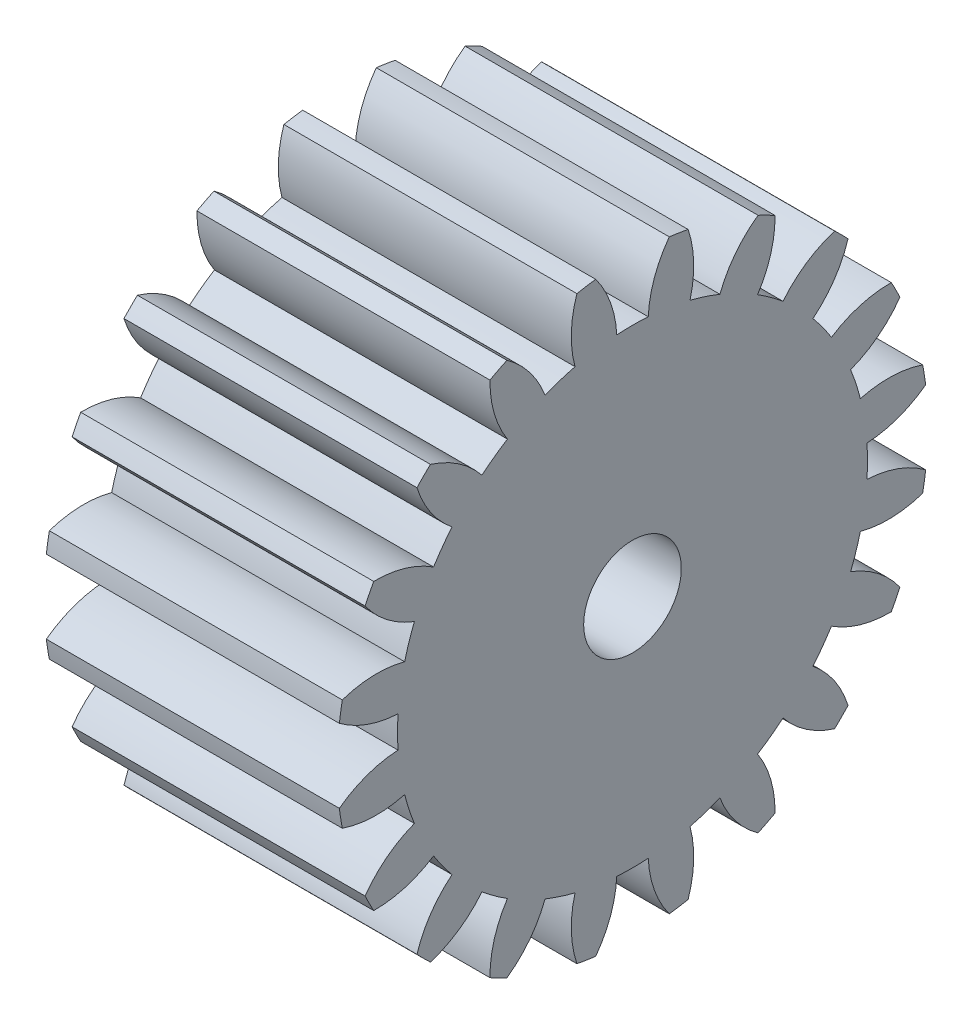
SolidWorks part; units mm, degrees
ref_plane "Plane1" through (0, 0, 0) normal (0, 0, 1) x (1, 0, 0)
ref_plane "Plane2" through (0, 0, 0) normal (0, 1, 0) x (1, 0, 0)
ref_plane "Plane3" through (0, 0, 0) normal (1, 0, 0) x (0, 0, -1)
sketch "HoldingSke" plane through (0, 0, 0) normal (0, 1, 0) x (1, 0, 0)
  line L0 (0, 0) -> (0.6834, -0.2487)
  line L1 (-15, 0) -> (100, 0) construction
  line L2 (0, 0) -> (-2.1039, 2.3779)
  line L3 (0, 0) -> (-11.863, 4.5341)
  line L4 (0, 0) -> (8.1152, 2.9537)
  line L5 (0, 0) -> (-46.8476, -17.4728)
  line L6 (0, 0) -> (-12.4344, -8.3896)
  line L7 (-2.1039, 2.3779) -> (8.6586, 51.2059)
  line L8 (-76.2, 54.61) -> (-75.3, 54.61)
  line L9 (-67.7845, 28.3722) -> (-49.3413, 33.142)
  line L10 (-76.2, 71.12) -> (104.1128, 71.12)
  line L11 (0, 0) -> (-15, 0)
  line L12 (-76.2, 101.6) -> (-76.151, 101.6)
  line L13 (24.9733, 27.94) -> (52.9518, 28.4284)
  line L14 (24.9733, 27.94) -> (24.9743, 27.94)
  line L15 (24.9733, 27.94) -> (100.4006, 29.5858)
  line L16 (-63.627, -1.375) -> (-12.827, -1.375)
  circle A0 centre (0, 0) radius 2.5
  circle A1 centre (0, 0) radius 12.0303
  circle A2 centre (0, 0) radius 37.5
  circle A3 centre (0, 0) radius 2.5
  dimension "MHD" = 24.0605
  dimension "Hub_dia" = 75
  dimension "Bore" = 5
  dimension "MBD" = 5
  dimension "Num_teeth" = 20
  dimension "Pitch" = 0.7273
  dimension "Overall_len" = 50
  dimension "Show_teeth" = 20
  dimension "Thickness" = 15
  dimension "OAL" = 50.0001
  dimension "T_dim" = 0.9
  dimension "Ap" = 14.5
  dimension "H" = 19.05
  dimension "Pitch_radius" = 180.3128
  dimension "Width" = 15
  dimension "Backlash" = 0.049
  dimension "Addendum_fac" = 1
  dimension "Dedendum_fac" = 1.25
  dimension "Clearance_fac" = 0.25
  dimension "Dedendum_add" = 0.001
  dimension "Module" = 1.375
sketch "BasProSke" plane through (0, 0, 0) normal (0, 1, 0) x (1, 0, 0)
  line L0 (-10, 0) -> (60, 0) construction
  line L1 (0, 0) -> (0, 15.125)
  line L2 (0, 0) -> (15, 0)
  line L3 (15, 0) -> (15, 15.125)
  line L4 (15, 15.125) -> (0, 15.125)
  dimension "Thickness" = 15
  dimension "Diameter" = 30.25
revolve "Base-Revolve" add sketch "BasProSke" angle 360 about L0
sketch "TooCutSke" plane through (0, 0, 0) normal (1, 0, 0) x (0, 0, -1)
  line L1 (0, 0) -> (0, 107) construction
  line L2 (0, 0) -> (-1.1645, 13.7006) construction
  line L3 (0, 0) -> (-4.2907, 27.0905) construction
  line L4 (-1.1645, 13.7006) -> (-2.1454, 13.5452) construction
  arc A0 (0.8054, 12.0033) -> (-0.8054, 12.0033) centre (0, 0) ccw
  arc A1 (1.9007, 15.0307) -> (-1.9007, 15.0307) centre (0, 0) ccw
  circle A2 centre (0, 0) radius 13.75 construction
  circle A3 centre (0, 0) radius 13.312 construction
  arc A4 (-0.8054, 12.0033) -> (-1.9007, 15.0307) centre (-6.2985, 11.7277) ccw
  arc A5 (1.9007, 15.0307) -> (0.8054, 12.0033) centre (6.2985, 11.7277) ccw
  dimension "Root_dia" = 24.0605
  dimension "Overcut_dia" = 30.3008
  dimension "Pitch_dia" = 27.5
  dimension "Base_dia" = 26.6241
  dimension "Flank_rad" = 5.5
  dimension "Half_ang" = 9
  dimension "Half_CT" = 0.9931
extrude "ToothCut" cut sketch "TooCutSke" along normal through all
fillet "Breaks" [suppressed] radius 0.0275
fillet "RootFillets" [suppressed] radius 0.3448
pattern_circular "TeethCuts" count 20 over 360 about axis through (0, 0, 0) along (1, 0, 0) of "ToothCut", "RootFillets", "Breaks"
sketch "HubNeaOneSke" plane through (0, 0, 0) normal (-1, 0, 0) x (0, 0, 1)
  circle A0 centre (0, 0) radius 12.0303
  dimension "Diameter" = 24.0605
extrude "HubNearOne" [suppressed] add sketch "HubNeaOneSke" along normal blind 35.0001
sketch "HubNeaBotSke" plane through (0, 0, 0) normal (-1, 0, 0) x (0, 0, 1)
  circle A0 centre (0, 0) radius 12.0303
  dimension "Diameter" = 24.0605
extrude "HubNearBoth" [suppressed] add sketch "HubNeaBotSke" along normal blind 17.5
ref_plane "FarPln" through (15, 0, 0) normal (1, 0, 0) x (0, 0, -1)
sketch "HubFarSke" plane through (15, 0, 0) normal (1, 0, 0) x (0, 0, -1)
  circle A0 centre (0, 0) radius 12.0303
  dimension "Diameter" = 24.0605
extrude "HubFar" [suppressed] add sketch "HubFarSke" along normal blind 17.5
sketch "BorSke" plane through (0, 0, 0) normal (1, 0, 0) x (0, 0, -1)
  circle A0 centre (0, 0) radius 2.5
  dimension "Diameter" = 5
extrude "Bore" cut sketch "BorSke" along normal mid plane 100.0001
sketch "KeySke" plane through (0, 0, 0) normal (1, 0, 0) x (0, 0, -1)
  line L0 (-1, 0) -> (-1, 3.4)
  line L1 (-1, 3.4) -> (1, 3.4)
  line L2 (1, 3.4) -> (1, 0)
  line L3 (0, 0) -> (0, 34) construction
  line L4 (-1, 0) -> (1, 0)
  dimension "Offset" = 3.4
  dimension "Width" = 2
extrude "Keyway" [suppressed] cut sketch "KeySke" along normal mid plane 100.0001
pattern_circular "Keyway2" [suppressed] count 2 every 90 about axis through (-10, 0, 0) along (1, 0, 0)
equation "' \"Module@HoldingSke\" = 6.35"
equation "' \"Num_teeth@HoldingSke\" = 12"
equation "' \"Ap@HoldingSke\" =  20"
equation "' \"Ap@HoldingSke\" = 20"
equation "' \"Width@HoldingSke\" = 0.5 * 25.4"
equation "' \"Hub_dia@HoldingSke\"= 1 * 25.4"
equation "' \"Hub_dia@HoldingSke\" = 1 * 25.4"
equation "' \"Overall_len@HoldingSke\" = 1.0 * 25.4"
equation "' \"Bore@HoldingSke\" = 0.75 * 25.4"
equation "' \"T_dim@HoldingSke\" = 0.1 * 25.4"
equation "' \"Width@KeySke\" = 0.25 * 25.4"
equation "' \"Show_teeth@HoldingSke\" = 13"
equation "' \"Backlash@HoldingSke\" = 0.009 * 25.4"
equation "' \"Addendum_fac@HoldingSke\" = 1.0"
equation "' \"Dedendum_fac@HoldingSke\" = 1.25"
equation "' \"Dedendum_add@HoldingSke\" = 0.00005 * 25.4"
equation "' \"Clearance_fac@HoldingSke\" = 0.25"
equation "\"Pitch@HoldingSke\" = 1 / \"Module@HoldingSke\""
equation "\"Overcut_dia@TooCutSke\" = (\"Num_teeth@HoldingSke\" + 2 * \"Addendum_fac@HoldingSke\") / \"Pitch@HoldingSke\" + 0.002 * 25.4"
equation "\"Pitch_dia@TooCutSke\" = \"Num_teeth@HoldingSke\" / \"Pitch@HoldingSke\""
equation "\"Base_dia@TooCutSke\" = \"Num_teeth@HoldingSke\" / \"Pitch@HoldingSke\" * cos((\"Ap@HoldingSke\"  * 3.14159265 / 180))"
equation "\"Root_dia@TooCutSke\" = (\"Num_teeth@HoldingSke\" + 2) / \"Pitch@HoldingSke\" - 2 * (\"Addendum_fac@HoldingSke\" + \"Dedendum_fac@HoldingSke\") / \"Pitch@HoldingSke\" - \"Dedendum_add@HoldingSke\" * 2"
equation "\"Half_ang@TooCutSke\" = 180 / \"Num_teeth@HoldingSke\""
equation "\"Half_CT@TooCutSke\" = \"Num_teeth@HoldingSke\" / \"Pitch@HoldingSke\" * sin((3.14159265 / 2 / \"Num_teeth@HoldingSke\")) / 2 - 7 * \"Backlash@HoldingSke\" / 4"
equation "\"Flank_rad@TooCutSke\" = \"Num_teeth@HoldingSke\" / \"Pitch@HoldingSke\" / 5"
equation "\"Radius@RootFillets\" = \"Clearance_fac@HoldingSke\" / \"Pitch@HoldingSke\" + \"Dedendum_add@HoldingSke\""
equation "\"Break_rad@Breaks\" = 0.02 / \"Pitch@HoldingSke\""
equation "\"Thickness@HoldingSke\" = \"Width@HoldingSke\""
equation "\"OAL@HoldingSke\" = \"Thickness@HoldingSke\""
equation "\"MHD@HoldingSke\" = (\"Num_teeth@HoldingSke\" + 2) / \"Pitch@HoldingSke\" - 2 * (\"Addendum_fac@HoldingSke\" + \"Dedendum_fac@HoldingSke\")  / \"Pitch@HoldingSke\" - \"Dedendum_add@HoldingSke\" * 2"
equation "\"MBD@HoldingSke\" = (\"Num_teeth@HoldingSke\" + 2) / \"Pitch@HoldingSke\" - 2 * (\"Addendum_fac@HoldingSke\" + \"Dedendum_fac@HoldingSke\")  / \"Pitch@HoldingSke\" - \"Dedendum_add@HoldingSke\" * 2 - 0.002 * 25.4"
equation "\"MHD@HoldingSke\" = ((sgn( \"MHD@HoldingSke\" - \"Hub_dia@HoldingSke\" )-1)*( \"MHD@HoldingSke\" - \"Hub_dia@HoldingSke\" ))/-2+ \"Hub_dia@HoldingSke\""
equation "\"MBD@HoldingSke\" = ((sgn( \"MBD@HoldingSke\" - \"Bore@HoldingSke\" )-1)*( \"MBD@HoldingSke\" - \"Bore@HoldingSke\" ))/-2+ \"Bore@HoldingSke\""
equation "\"OAL@HoldingSke\" = ((sgn( \"OAL@HoldingSke\" - \"Overall_len@HoldingSke\" )+1)*( \"OAL@HoldingSke\" - \"Overall_len@HoldingSke\" ))/2 + \"Overall_len@HoldingSke\" + 0.000002 * 25.4"
equation "\"Num_teeth@TeethCuts\" = int( \"Show_teeth@HoldingSke\" ) + 1"
equation "\"Num_teeth@TeethCuts\" = ((sgn( \"Num_teeth@TeethCuts\" - \"Num_teeth@HoldingSke\" )-1)*( \"Num_teeth@TeethCuts\" - \"Num_teeth@HoldingSke\" ))/-2+ \"Num_teeth@HoldingSke\""
equation "\"Num_teeth@TeethCuts\" = ((sgn( \"Num_teeth@TeethCuts\" - 2.0)+1)*( \"Num_teeth@TeethCuts\" - 2.0))/2 +2.0"
equation "\"Angle@TeethCuts\" = 360.0 / \"Num_teeth@HoldingSke\""
equation "\"Diameter@BasProSke\" = (\"Num_teeth@HoldingSke\" + 2 * \"Addendum_fac@HoldingSke\") / \"Pitch@HoldingSke\""
equation "\"Thickness@BasProSke\"  = \"Thickness@HoldingSke\""
equation "' \"Fillet_rad@BasProSke\" =  \"Thickness@HoldingSke\" * 0.05"
equation "' \"Fillet_rad@BasProSke\" = \"Thickness@HoldingSke\" * 0.05"
equation "\"MHD@HoldingSke\" = ((sgn( \"MHD@HoldingSke\" - \"Root_dia@TooCutSke\" )-1)*( \"MHD@HoldingSke\" - \"Root_dia@TooCutSke\" ))/-2+ \"Root_dia@TooCutSke\""
equation "\"Diameter@HubNeaOneSke\" = \"MHD@HoldingSke\""
equation "\"Length@HubNearOne\" = \"OAL@HoldingSke\" - \"Thickness@BasProSke\""
equation "\"Diameter@HubNeaBotSke\" = \"MHD@HoldingSke\""
equation "\"Length@HubNearBoth\" = ( \"OAL@HoldingSke\" - \"Thickness@BasProSke\" ) / 2.0"
equation "\"Thickness@FarPln\" = \"Thickness@BasProSke\""
equation "\"Diameter@HubFarSke\" = \"MHD@HoldingSke\""
equation "\"Length@HubFar\" = ( \"OAL@HoldingSke\" - \"Thickness@BasProSke\" ) / 2.0"
equation "\"Diameter@BorSke\" = \"MBD@HoldingSke\""
equation "\"D1@Bore\" = \"OAL@HoldingSke\" * 2.0"
equation "\"D1@Keyway\" = \"OAL@HoldingSke\" * 2.0"
equation "\"Offset@KeySke\" = \"T_dim@HoldingSke\" + \"MBD@HoldingSke\" / 2.0"
